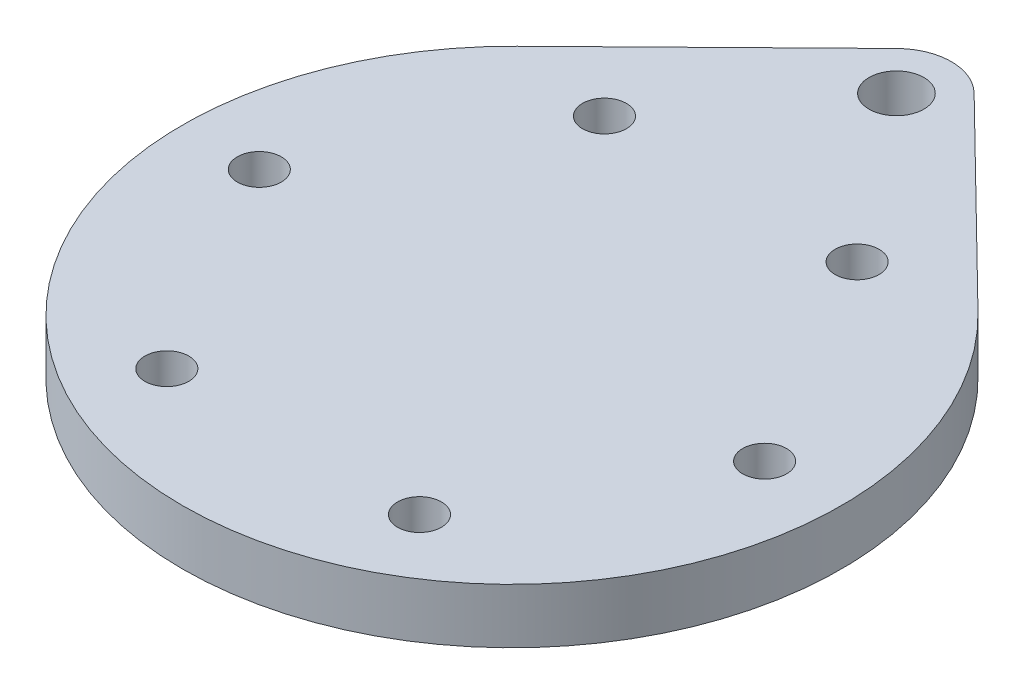
SolidWorks part; units mm, degrees
ref_plane "Front Plane" through (0, 0, 0) normal (0, 0, 1) x (1, 0, 0)
ref_plane "Top Plane" through (0, 0, 0) normal (0, 1, 0) x (1, 0, 0)
ref_plane "Right Plane" through (0, 0, 0) normal (1, 0, 0) x (0, 0, -1)
sketch "Sketch1" plane through (0, 0, 0) normal (0, 1, 0) x (1, 0, 0)
  line L0 (0, 35) -> (0, 0) construction
  line L1 (-3.4993, 38.5714) -> (-20.9956, 21.4286)
  line L2 (3.4993, 38.5714) -> (20.9956, 21.4286)
  circle A0 centre (0, 0) radius 30
  circle A1 centre (0, 0) radius 23 construction
  circle A2 centre (0, 35) radius 2.5
  circle A3 centre (0, 35) radius 5
  circle A16 centre (23, 0) radius 2
  circle A17 centre (11.5, -19.9186) radius 2
  circle A18 centre (-11.5, -19.9186) radius 2
  circle A19 centre (-23, 0) radius 2
  circle A20 centre (-11.5, 19.9186) radius 2
  circle A21 centre (11.5, 19.9186) radius 2
  point P25 (0, 0)
  point P38 (0, 0)
  dimension "D1" = 60
  dimension "D2" = 46
  dimension "D4" = 5
  dimension "D5" = 4
  dimension "D3" = 35
  dimension "D6" = 6
extrude "Boss-Extrude1" add sketch "Sketch1" along normal blind 5
